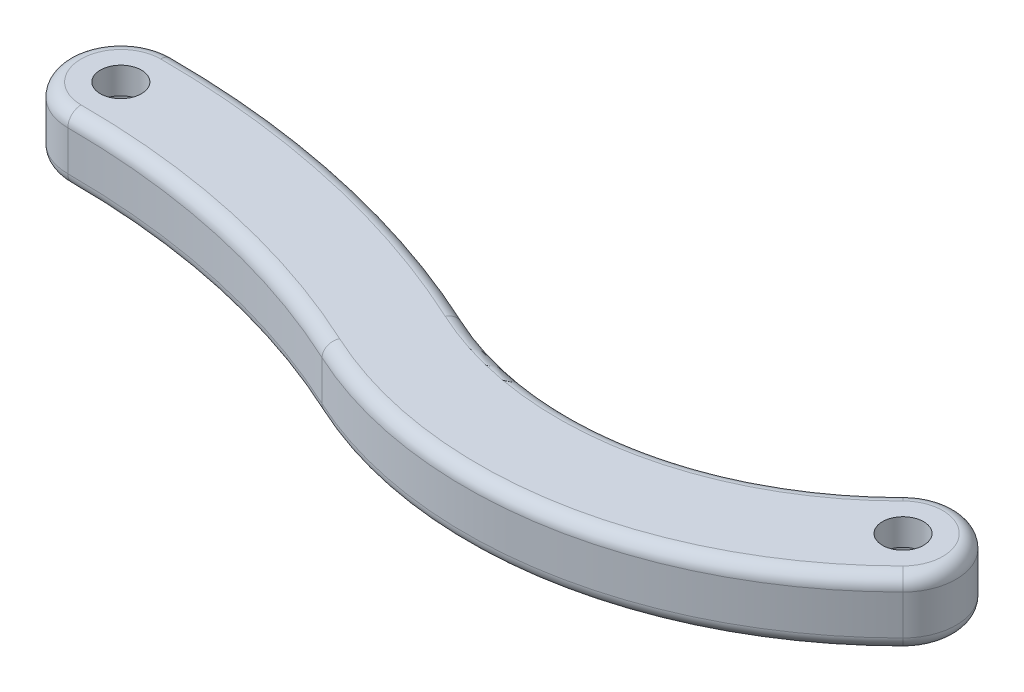
SolidWorks part; units mm, degrees
material "Rubber"
ref_plane "Front Plane" through (0, 0, 0) normal (0, 0, 1) x (1, 0, 0)
ref_plane "Top Plane" through (0, 0, 0) normal (0, 1, 0) x (1, 0, 0)
ref_plane "Right Plane" through (0, 0, 0) normal (1, 0, 0) x (0, 0, -1)
sketch "Sketch1" plane through (0, 0, 0) normal (0, 1, 0) x (1, 0, 0)
  line L0 (-29.5, 0) -> (29.5, 0) construction
  line L3 (26.029, 3.471) -> (-3.1174, 32.6174) construction
  circle A2 centre (-29.5, 0) radius 1.55
  circle A3 centre (29.5, 0) radius 1.55
  arc A4 (-29.5, 4) -> (-29.5, -4) centre (-29.5, 0) ccw
  arc A5 (32.3284, -2.8284) -> (26.6716, 2.8284) centre (29.5, 0) ccw
  arc A7 (-1.5267, -2.1725) -> (26.6716, 2.8284) centre (8.9939, 20.5061) ccw
  arc A9 (-4.8932, -9.4296) -> (32.3284, -2.8284) centre (8.9939, 20.5061) ccw
  arc A10 (-29.5, 4) -> (-1.5267, -2.1725) centre (-29.5, -62.4731) cw
  arc A11 (-29.5, -4) -> (-4.8932, -9.4296) centre (-29.5, -62.4731) cw
  dimension "D1" = 3.1
  dimension "D8" = 33
  dimension "D2" = 59
  dimension "D3" = 29.5
  dimension "D4" = 8
  dimension "D6" = 8
  dimension "D5" = 45
  dimension "D7" = 8
extrude "Boss-Extrude1" add sketch "Sketch1" along normal blind 5
fillet "Fillet1" radius 1 12 edges at (32.3284, 5, -2.8284) (14.7565, 5, 11.9869) (-16.9007, 5, 5.3735) (-33.5, 5, 0) (-15.1769, 5, -2.4385) (32.3284, 0, -2.8284) (14.7565, 0, 11.9869) (-16.9007, 0, 5.3735) (-33.5, 0, 0) (-15.1769, 0, -2.4385) (13.3595, 5, 4.1098) (13.3595, 0, 4.1098)
sketch "Sketch2" plane through (0, 0, 0) normal (0, -1, 0) x (1, 0, 0)
  circle A0 centre (29.5, 0) radius 2.9
  circle A1 centre (-29.5, 0) radius 2.9
  dimension "D2" = 5.8
extrude "Cut-Extrude1" cut sketch "Sketch2" against normal blind 3
equation "\"D3@Sketch1\"=\"D2@Sketch1\"/2"
